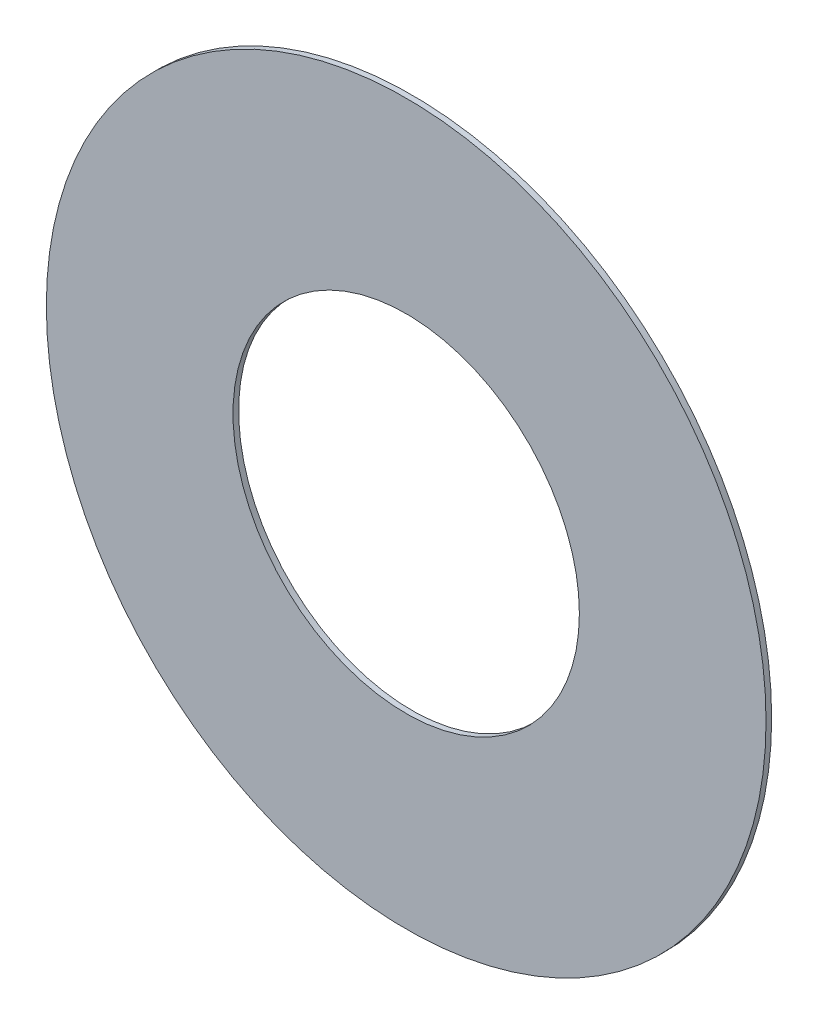
SolidWorks part; units mm, degrees
material "Polyester Resin"
ref_plane "Front Plane" through (0, 0, 0) normal (0, 0, 1) x (1, 0, 0)
ref_plane "Top Plane" through (0, 0, 0) normal (0, 1, 0) x (1, 0, 0)
ref_plane "Right Plane" through (0, 0, 0) normal (1, 0, 0) x (0, 0, -1)
sketch "Sketch1" plane through (0, 0, 0) normal (0, 0, 1) x (1, 0, 0)
  circle A0 centre (0, 0) radius 9.779
  circle A1 centre (0, 0) radius 20.32
  dimension "D1" = 19.558
  dimension "D2" = 40.64
extrude "Boss-Extrude1" add sketch "Sketch1" along normal blind 0.3175
